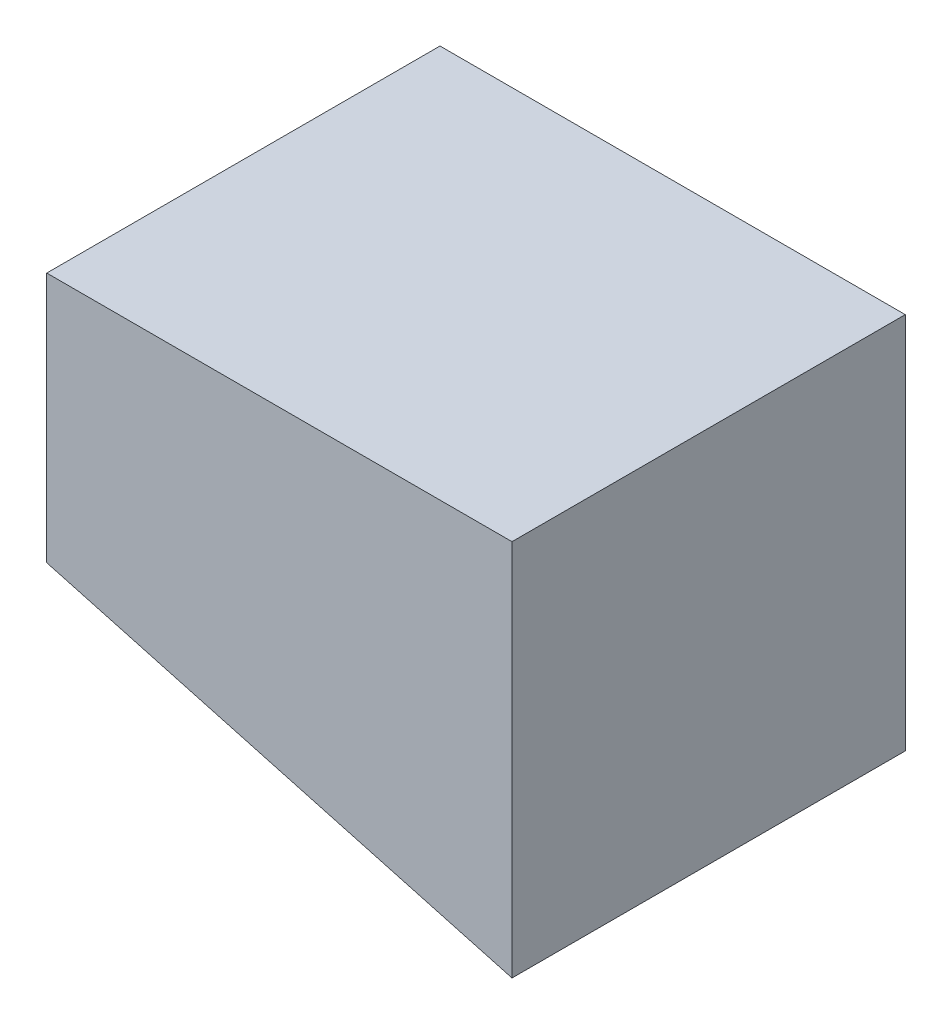
SolidWorks part; units mm, degrees
ref_plane "Front Plane" through (0, 0, 0) normal (0, 0, 1) x (1, 0, 0)
ref_plane "Top Plane" through (0, 0, 0) normal (0, 1, 0) x (1, 0, 0)
ref_plane "Right Plane" through (0, 0, 0) normal (1, 0, 0) x (0, 0, -1)
sketch "Sketch1" plane through (0, 0, 0) normal (0, 1, 0) x (1, 0, 0)
  line L1 (-246.25, -208.135) -> (246.25, -208.135)
  line L2 (-246.25, -208.135) -> (-246.25, 208.135)
  line L3 (-246.25, 208.135) -> (246.25, 208.135)
  line L4 (246.25, -208.135) -> (246.25, 208.135)
  line L5 (-246.25, -208.135) -> (246.25, 208.135) construction
  line L6 (-246.25, 208.135) -> (246.25, -208.135) construction
  point P0 (0, 0)
  dimension "D1" = 416.27
  dimension "D2" = 492.5
extrude "Boss-Extrude1" add sketch "Sketch1" along normal blind 400
sketch "Sketch3" plane through (0, 0, 208.135) normal (0, 0, 1) x (1, 0, 0)
  line L0 (246.25, 0) -> (-246.25, 134.4392)
  line L1 (-246.25, 400) -> (-246.25, 0) construction
  line L2 (-246.25, 134.4392) -> (-246.25, 0)
  line L3 (-246.25, 0) -> (246.25, 0)
  dimension "D1" = 15.268
extrude "Cut-Extrude2" cut sketch "Sketch3" against normal through all
